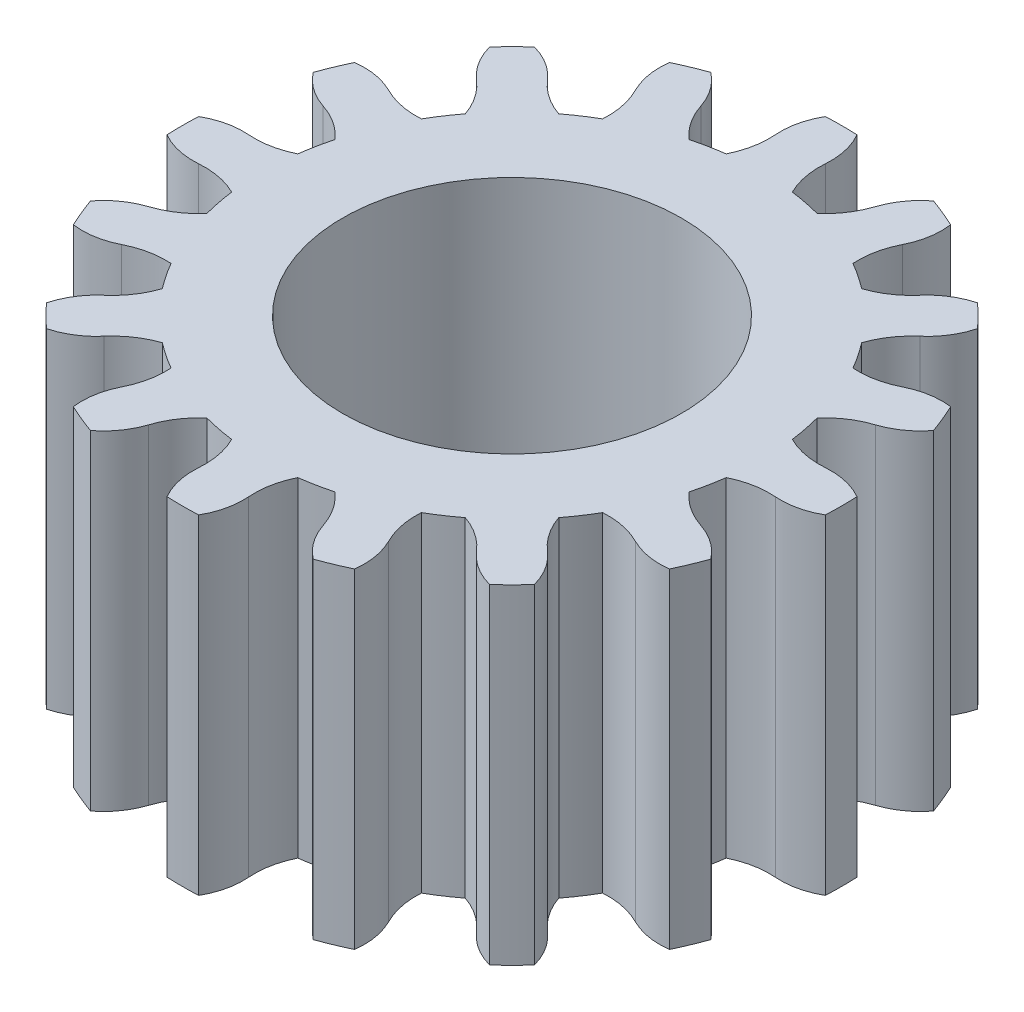
SolidWorks part; units mm, degrees
ref_plane "Front Plane" through (0, 0, 0) normal (0, 0, 1) x (1, 0, 0)
ref_plane "Top Plane" through (0, 0, 0) normal (0, 1, 0) x (1, 0, 0)
ref_plane "Right Plane" through (0, 0, 0) normal (1, 0, 0) x (0, 0, -1)
sketch "Sketch1" plane through (0, 0, 0) normal (0, 1, 0) x (1, 0, 0)
  circle A0 centre (0, 0) radius 3.175
  circle A1 centre (0, 0) radius 1.632
  dimension "D1" = 6.35
  dimension "D2" = 3.2639
extrude "Boss-Extrude1" add sketch "Sketch1" along normal blind 3.175
sketch "Sketch2" plane through (0, 3.175, 0) normal (0, 1, 0) x (1, 0, 0)
  line L0 (-1.215, 2.9333) -> (0, 0) construction
  line L1 (0, 0) -> (0, 3.175) construction
  line L2 (-0.6194, 3.114) -> (0, 0) construction
  line L3 (-0.1524, 3.1713) -> (0, 0) construction
  line L4 (0, -1.632) -> (0, -3.175) construction
  line L5 (2.4035, 0) -> (3.175, 0) construction
  circle A0 centre (0, 0) radius 3.175 construction
  arc A1 (-1.215, 2.9333) -> (-1.0728, 2.9883) centre (0, 0) cw construction
  arc A2 (0, 3.175) -> (-0.1524, 3.1713) centre (0, 0) ccw construction
  arc A3 (-0.1524, 3.1713) -> (-1.0728, 2.9883) centre (0, 0) ccw construction
  arc A4 (-0.1524, 3.1713) -> (-0.2417, 2.7787) centre (0.4367, 2.8309) ccw
  arc A5 (-0.2417, 2.7787) -> (-0.3186, 2.3823) centre (-1.0015, 2.7203) cw
  arc A6 (-0.3186, 2.3823) -> (-0.6173, 2.3228) centre (0, 0) ccw
  circle A7 centre (0, 0) radius 2.4035 construction
  circle A8 centre (0, 0) radius 1.632 construction
  circle A9 centre (0, 0) radius 2.7892
  arc A10 (-0.8401, 2.6597) -> (-0.6173, 2.3228) centre (-0.1158, 2.8965) ccw
  arc A11 (-1.0728, 2.9883) -> (-0.8401, 2.6597) centre (-1.4868, 2.4483) cw
  arc A12 (-1.0728, 2.9883) -> (-0.1524, 3.1713) centre (0, 0) cw
  point P20 (0, -2.4035)
  point P23 (2.7892, 0)
  circle M9 centre (0, 0) radius 3.175
  dimension "D3" = 0.762
  dimension "D5" = 0.1524
  dimension "D1" = 22.5
  dimension "D2" = 11.25
  dimension "D4" = 0.3046
extrude "Cut-Extrude1" cut sketch "Sketch2" against normal through all contours A9 A10 A6 A5 | A11 A9 A4 M9
pattern_circular "CirPattern1" count 16 over 360 about axis through (0, 0, 0) along (0, 1, 0) of "Cut-Extrude1"
